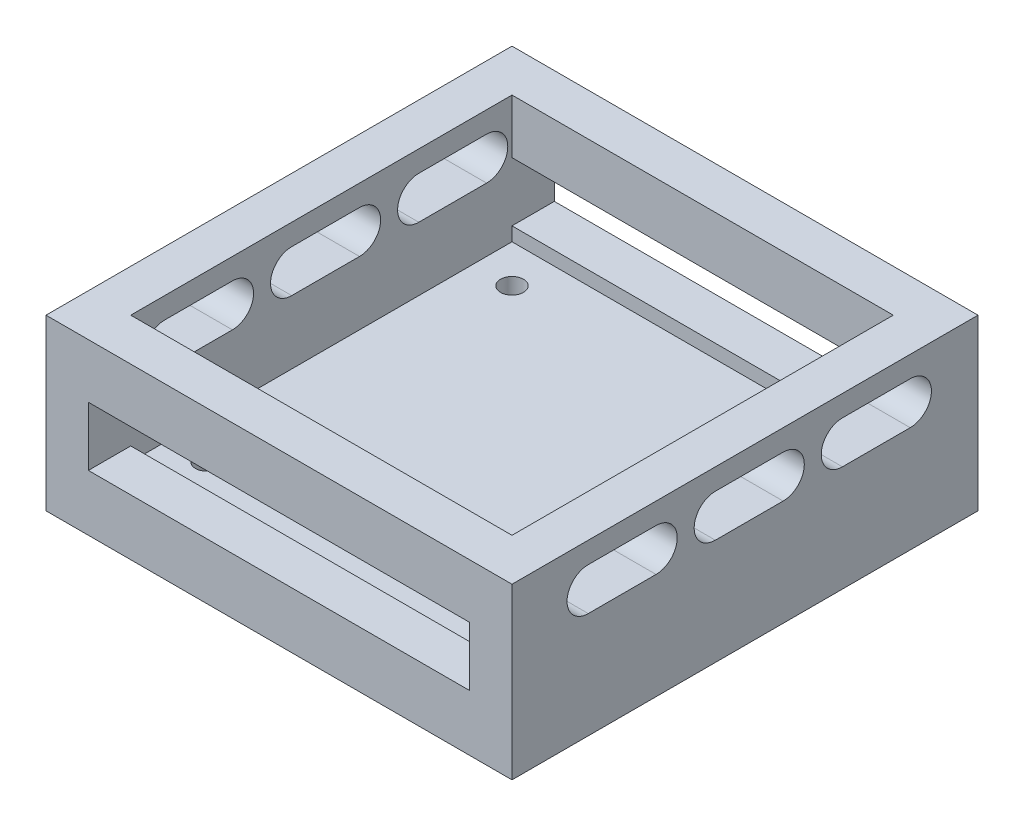
SolidWorks part; units mm, degrees
ref_plane "Front Plane" through (0, 0, 0) normal (0, 0, 1) x (1, 0, 0)
ref_plane "Top Plane" through (0, 0, 0) normal (0, 1, 0) x (1, 0, 0)
ref_plane "Right Plane" through (0, 0, 0) normal (1, 0, 0) x (0, 0, -1)
sketch "Sketch1" plane through (0, 0, 0) normal (0, 1, 0) x (1, 0, 0)
  line L1 (22.5, 22.5) -> (-22.5, 22.5)
  line L2 (22.5, 22.5) -> (22.5, -22.5)
  line L3 (22.5, -22.5) -> (-22.5, -22.5)
  line L4 (-22.5, 22.5) -> (-22.5, -22.5)
  line L5 (0, -22.5) -> (0, 22.5) construction
  line L6 (22.5, 0) -> (-22.5, 0) construction
  line L7 (18, 18) -> (-18, 18) construction
  line L8 (18, 18) -> (18, -18) construction
  line L9 (18, -18) -> (-18, -18) construction
  line L10 (-18, 18) -> (-18, -18) construction
  line L11 (0, -18) -> (0, 18) construction
  line L12 (18, 0) -> (-18, 0) construction
  circle A0 centre (-18, 18) radius 1.35
  circle A1 centre (18, 18) radius 1.35
  circle A2 centre (18, -18) radius 1.35
  circle A3 centre (-18, -18) radius 1.35
  point P0 (0, 0)
  point P4 (0, 0)
  dimension "D5" = 2.7
  dimension "D1" = 45
  dimension "D2" = 45
  dimension "D3" = 36
  dimension "D4" = 36
extrude "Boss-Extrude1" add sketch "Sketch1" along normal blind 5
sketch "Sketch2" plane through (0, 0, 0) normal (0, 1, 0) x (1, 0, 0)
  line L8 (-27.5, 27.5) -> (-27.5, -27.5)
  line L9 (-27.5, -27.5) -> (27.5, -27.5)
  line L10 (27.5, -27.5) -> (27.5, 27.5)
  line L11 (27.5, 27.5) -> (-27.5, 27.5)
  line L12 (-27.5, 27.5) -> (-27.5, -27.5)
  line L13 (-27.5, -27.5) -> (27.5, -27.5)
  line L14 (27.5, -27.5) -> (27.5, 27.5)
  line L15 (27.5, 27.5) -> (-27.5, 27.5)
  line L16 (-22.5, 22.5) -> (-22.5, -22.5)
  line L17 (-22.5, -22.5) -> (22.5, -22.5)
  line L18 (22.5, -22.5) -> (22.5, 22.5)
  line L19 (22.5, 22.5) -> (-22.5, 22.5)
  line L20 (-22.5, 22.5) -> (-22.5, -22.5)
  line L21 (-22.5, -22.5) -> (22.5, -22.5)
  line L22 (22.5, -22.5) -> (22.5, 22.5)
  line L23 (22.5, 22.5) -> (-22.5, 22.5)
  dimension "D1" = 5
  dimension "D2" = 0
extrude "Boss-Extrude2" add sketch "Sketch2" along normal blind 20
sketch "Sketch3" plane through (0, 0, -27.5) normal (0, 0, -1) x (-1, 0, 0)
  line L0 (0, 0) -> (0, 5) construction
  line L1 (-27.5, 20) -> (-27.5, 0) construction
  line L2 (-22.5, 13.6008) -> (22.5, 13.6008)
  line L3 (-22.5, 13.6008) -> (-22.5, 6.631)
  line L4 (-22.5, 6.631) -> (22.5, 6.631)
  line L5 (22.5, 13.6008) -> (22.5, 6.631)
  line L6 (27.5, 20) -> (27.5, 0) construction
  dimension "D1" = 5
  dimension "D2" = 5
  dimension "D3" = 5
extrude "Cut-Extrude1" cut sketch "Sketch3" against normal through all
sketch "Sketch4" plane through (-27.5, 0, 0) normal (-1, 0, 0) x (0, 0, 1)
  line L0 (-15.5, 15) -> (-15.5, 20) construction
  line L1 (-27.5, 20) -> (27.5, 20) construction
  line L2 (-11.5, 15) -> (-19.5, 15) construction
  line L3 (-11.5, 12.5) -> (-19.5, 12.5)
  line L4 (-11.5, 17.5) -> (-19.5, 17.5)
  line L5 (-19.5, 15) -> (-27.5, 15) construction
  line L6 (-27.5, 20) -> (-27.5, 0) construction
  line L13 (3.5, 17.5) -> (-4.5, 17.5)
  line L16 (3.5, 12.5) -> (-4.5, 12.5)
  line L17 (3.5, 15) -> (-4.5, 15) construction
  line L18 (18.5, 17.5) -> (10.5, 17.5)
  line L19 (18.5, 12.5) -> (10.5, 12.5)
  line L20 (18.5, 15) -> (10.5, 15) construction
  arc A0 (-11.5, 12.5) -> (-11.5, 17.5) centre (-11.5, 15) ccw
  arc A1 (-19.5, 17.5) -> (-19.5, 12.5) centre (-19.5, 15) ccw
  arc A10 (3.5, 12.5) -> (3.5, 17.5) centre (3.5, 15) ccw
  arc A11 (-4.5, 17.5) -> (-4.5, 12.5) centre (-4.5, 15) ccw
  arc A12 (18.5, 12.5) -> (18.5, 17.5) centre (18.5, 15) ccw
  arc A13 (10.5, 17.5) -> (10.5, 12.5) centre (10.5, 15) ccw
  point P7 (-15.5, 15)
  point P18 (-0.5, 15)
  point P25 (14.5, 15)
  dimension "D3" = 2.5
  dimension "D1" = 8
  dimension "D2" = 8
  dimension "D4" = 5
extrude "Cut-Extrude2" cut sketch "Sketch4" against normal through all
sketch "Sketch5" plane through (0, 0, -30) normal (0, 0, -1) x (-1, 0, 0)
  line L0 (0, 35) -> (0, 30) construction
  line L1 (-42.5, 35) -> (42.5, 35) construction
  line L2 (-7.5, 30) -> (7.5, 30) construction
  line L3 (-7.5, 33) -> (7.5, 33)
  line L4 (-7.5, 27) -> (7.5, 27)
  arc A0 (-7.5, 33) -> (-7.5, 27) centre (-7.5, 30) ccw
  arc A1 (7.5, 27) -> (7.5, 33) centre (7.5, 30) ccw
  point P7 (0, 30)
  dimension "D2" = 3
  dimension "D1" = 5
  dimension "D3" = 15
extrude "Cut-Extrude3" cut sketch "Sketch5" against normal through all
